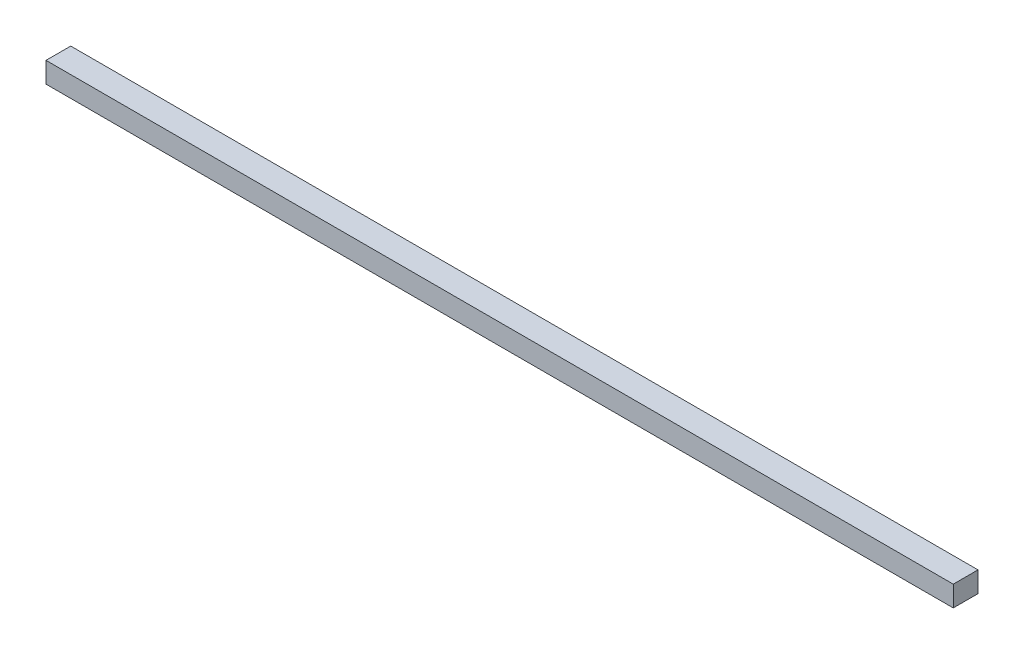
SolidWorks part; units mm, degrees
material "Maple"
ref_plane "Front Plane" through (0, 0, 0) normal (0, 0, 1) x (1, 0, 0)
ref_plane "Top Plane" through (0, 0, 0) normal (0, 1, 0) x (1, 0, 0)
ref_plane "Right Plane" through (0, 0, 0) normal (1, 0, 0) x (0, 0, -1)
sketch "Sketch1" plane through (0, 0, 0) normal (1, 0, 0) x (0, 0, -1)
  line L1 (-9.525, 7.9375) -> (9.525, 7.9375)
  line L2 (-9.525, 7.9375) -> (-9.525, -7.9375)
  line L3 (-9.525, -7.9375) -> (9.525, -7.9375)
  line L4 (9.525, 7.9375) -> (9.525, -7.9375)
  line L5 (-9.525, 7.9375) -> (9.525, -7.9375) construction
  line L6 (-9.525, -7.9375) -> (9.525, 7.9375) construction
  point P0 (0, 0)
  dimension "D1" = 15.875
  dimension "D2" = 19.05
extrude "Boss-Extrude1" add sketch "Sketch1" along normal mid plane 698.5
